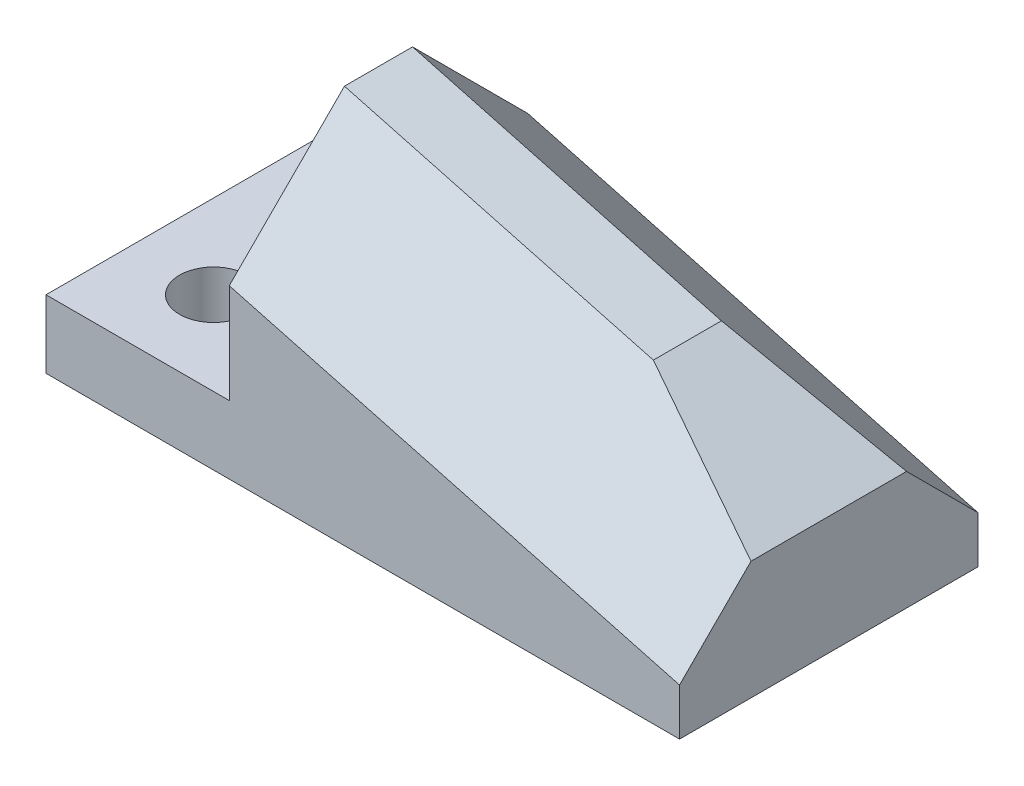
SolidWorks part; units mm, degrees
ref_plane "Front Plane" through (0, 0, 0) normal (0, 0, 1) x (1, 0, 0)
ref_plane "Top Plane" through (0, 0, 0) normal (0, 1, 0) x (1, 0, 0)
ref_plane "Right Plane" through (0, 0, 0) normal (1, 0, 0) x (0, 0, -1)
sketch "Sketch1" plane through (0, 0, 0) normal (0, 0, 1) x (1, 0, 0)
  line L0 (0, -34.8928) -> (0, 84.3697) construction
  line L1 (-60.5, 0) -> (60.5, 0)
  line L2 (-60.5, 0) -> (-60.5, 13)
  line L3 (-60.5, 13) -> (60.5, 13)
  line L4 (60.5, 0) -> (60.5, 13)
  dimension "D1" = 121
  dimension "D2" = 13
extrude "Boss-Extrude1" add sketch "Sketch1" along normal mid plane 57
sketch "Sketch2" plane through (0, 13, 0) normal (0, 1, 0) x (1, 0, 0)
  line L0 (-60.5, -28.5) -> (-60.5, 28.5) construction
  line L1 (60.5, -28.5) -> (-60.5, -28.5) construction
  circle A0 centre (-44.5, 12.5) radius 6.5
  circle A1 centre (-44.5, -12.5) radius 6.5
  dimension "D4" = 13
  dimension "D1" = 25
  dimension "D2" = 16
  dimension "D3" = 16
extrude "Cut-Extrude1" cut sketch "Sketch2" against normal through all
sketch "Sketch3" plane through (0, 0, 28.5) normal (0, 0, 1) x (1, 0, 0)
  line L0 (-60.5, 13) -> (-60.5, 0) construction
  line L1 (-25.5, 13) -> (-25.5, 54)
  line L3 (-25.5, 54) -> (33.5, 38.191)
  line L4 (33.5, 38.191) -> (60.5, 22.6025)
  line L5 (60.5, 22.6025) -> (60.5, 13)
  line L6 (-25.5, 13) -> (60.5, 13)
  line L8 (-25.5, 54) -> (35, 54) construction
  line L9 (33.5, 38.191) -> (55.1722, 38.191) construction
  line L12 (-60.5, 0) -> (60.5, 0) construction
  dimension "D1" = 15
  dimension "D2" = 30
  dimension "D3" = 35
  dimension "D4" = 54
  dimension "D5" = 27
extrude "Boss-Extrude2" add sketch "Sketch3" against normal blind 57
sketch "Sketch5" plane through (0, 0, 28.5) normal (0, 0, 1) x (1, 0, 0)
  line L0 (-25.5, 32) -> (60.5, 8.9564)
  line L1 (-25.5, 54) -> (-25.5, 13) construction
  line L2 (60.5, 0) -> (60.5, 22.6025) construction
  line L3 (33.5, 38.191) -> (-25.5, 54) construction
  dimension "D1" = 22
sketch "Sketch6" plane through (11.7918, 44.0077, 0) normal (0.2588, 0.9659, 0) x (0.9659, -0.2588, 0)
  line L0 (-38.6073, 0) -> (22.474, 0) construction
  line L1 (-38.6073, 28.5) -> (-38.6073, -28.5) construction
  line L2 (22.474, 28.5) -> (22.474, -28.5) construction
  line L4 (-38.6073, 6.5) -> (22.474, 6.5)
  line L5 (-38.6073, 6.5) -> (-38.6073, -6.5)
  line L6 (-38.6073, -6.5) -> (22.474, -6.5)
  line L7 (22.474, 6.5) -> (22.474, -6.5)
  dimension "D1" = 13
ref_plane "Plane1" through (6.9409, 25.9037, 25.9037) normal (0.1862, 0.6947, 0.6947) x (0.9825, -0.1316, -0.1316)
sketch "Sketch7" plane through (6.9409, 25.9037, 25.9037) normal (0.1862, 0.6947, 0.6947) x (0.9825, -0.1316, -0.1316)
  line L0 (-40.9514, -0.6272) -> (-40.9514, 40.506)
  line L1 (-40.9514, 40.506) -> (61.9418, 20.9802)
  line L2 (61.9418, 20.9802) -> (61.9418, -20.153)
  line L3 (61.9418, -20.153) -> (-40.9514, -0.6272)
extrude "Cut-Extrude3" cut sketch "Sketch7" along normal up to next
sketch "Sketch9" plane through (0, 0, -28.5) normal (0, 0, -1) x (-1, 0, 0)
  line L0 (25.5, 32) -> (-60.5, 8.9564)
  line L1 (25.5, 54) -> (25.5, 13) construction
  line L2 (-60.5, 0) -> (-60.5, 22.6025) construction
  line L3 (-33.5, 38.191) -> (25.5, 54) construction
  dimension "D1" = 22
ref_plane "Plane3" through (6.9409, 25.9037, -25.9037) normal (0.1862, 0.6947, -0.6947) x (-0.9825, 0.1316, -0.1316)
sketch "Sketch10" plane through (6.9409, 25.9037, -25.9037) normal (0.1862, 0.6947, -0.6947) x (-0.9825, 0.1316, -0.1316)
  line L0 (44.9886, 4.7033) -> (44.9886, 35.816)
  line L1 (44.9886, 35.816) -> (-66.9181, 14.9838)
  line L2 (33.018, 33.5876) -> (-27.0316, 22.4089) construction
  line L3 (44.9886, 35.816) -> (-78.6652, 12.797) construction
  line L4 (44.9886, 4.7033) -> (-66.9181, -16.1289)
  line L5 (-66.9181, -16.1289) -> (-66.9181, 14.9838)
  line L6 (33.018, 2.4749) -> (-54.512, -13.8194) construction
  point P0 (0, 0)
  point P4 (-53.7319, 17.4385)
  point P7 (0, 0)
  point P8 (33.018, 33.5876)
  point P11 (33.018, 33.5876)
  point P13 (0, 0)
  point P14 (45.4035, 35.8932)
  point P15 (0, 0)
extrude "Cut-Extrude4" cut sketch "Sketch10" along normal up to next
